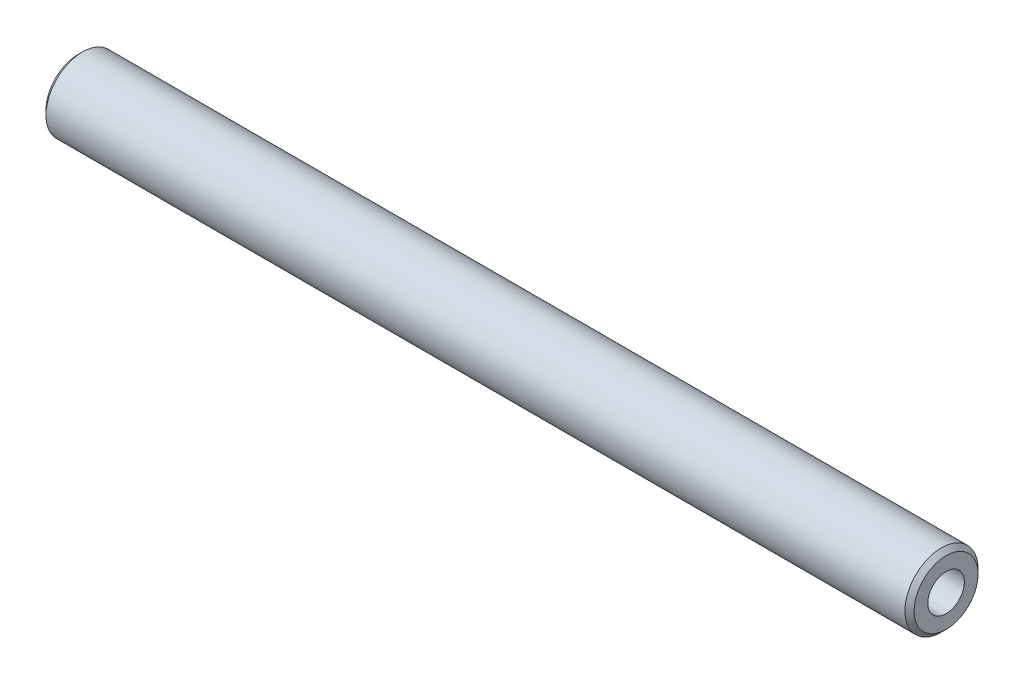
SolidWorks part; units mm, degrees
material "1.4301 (X5CrNi18-10)"
ref_plane "正面" through (0, 0, 0) normal (0, 0, 1) x (1, 0, 0)
ref_plane "平面" through (0, 0, 0) normal (0, 1, 0) x (1, 0, 0)
ref_plane "右側面" through (0, 0, 0) normal (1, 0, 0) x (0, 0, -1)
sketch "ｽｹｯﾁ1" plane through (0, 0, 0) normal (0, 0, 1) x (1, 0, 0)
  line L0 (0, 0) -> (21203.2319, 0) construction
  line L2 (-47.5, 0) -> (47.5, 0)
  line L3 (-47.5, 0) -> (-47.5, 4)
  line L4 (-47.5, 4) -> (47.5, 4)
  line L5 (47.5, 0) -> (47.5, 4)
  point P7 (0, 0)
  dimension "D1" = 8
  dimension "D2" = 95
revolve "回転1" add sketch "ｽｹｯﾁ1" angle 360 about L0
hole_wizard "M4x0.7 ねじ穴1" positions "3Dｽｹｯﾁ1" profile "ｽｹｯﾁ3" tap size "M4x0.7" standard "JIS"
sketch3d "3Dｽｹｯﾁ1"
  line L0 (47.5, 0, 0) -> (-47.5, 0, 0) construction
  point P0 (47.5, 0, 0)
  point P4 (-47.5, 0, 0)
sketch "ｽｹｯﾁ3" plane through (47.5, 0, 0) normal (0, 1, 0) x (0, 0, -1)
  line L0 (0, 0) -> (0, 12.4914)
  line L1 (0, 12.4914) -> (1.65, 11.5)
  line L2 (1.65, 11.5) -> (1.65, 8)
  line L3 (1.65, 8) -> (2, 8)
  line L4 (2, 8) -> (2, 0)
  line L5 (2, 0) -> (0, 0)
  line L10 (0, 12.4914) -> (-1.65, 11.5) construction
  line L11 (0, -6.35) -> (0, 107.95) construction
  dimension "ねじ下穴ﾄﾞﾘﾙ直径" = 3.3
  dimension "ねじ下穴ﾄﾞﾘﾙの深さ" = 11.5
  dimension "ねじ山の主要直径" = 4
  dimension "ねじ山の深さ" = 8
  dimension "ﾄﾞﾘﾙ角度" = 118
chamfer "面取り1" distance 0.5 angle 45 2 edges at (-47.5, 0, 4) (47.5, 0, 4)
